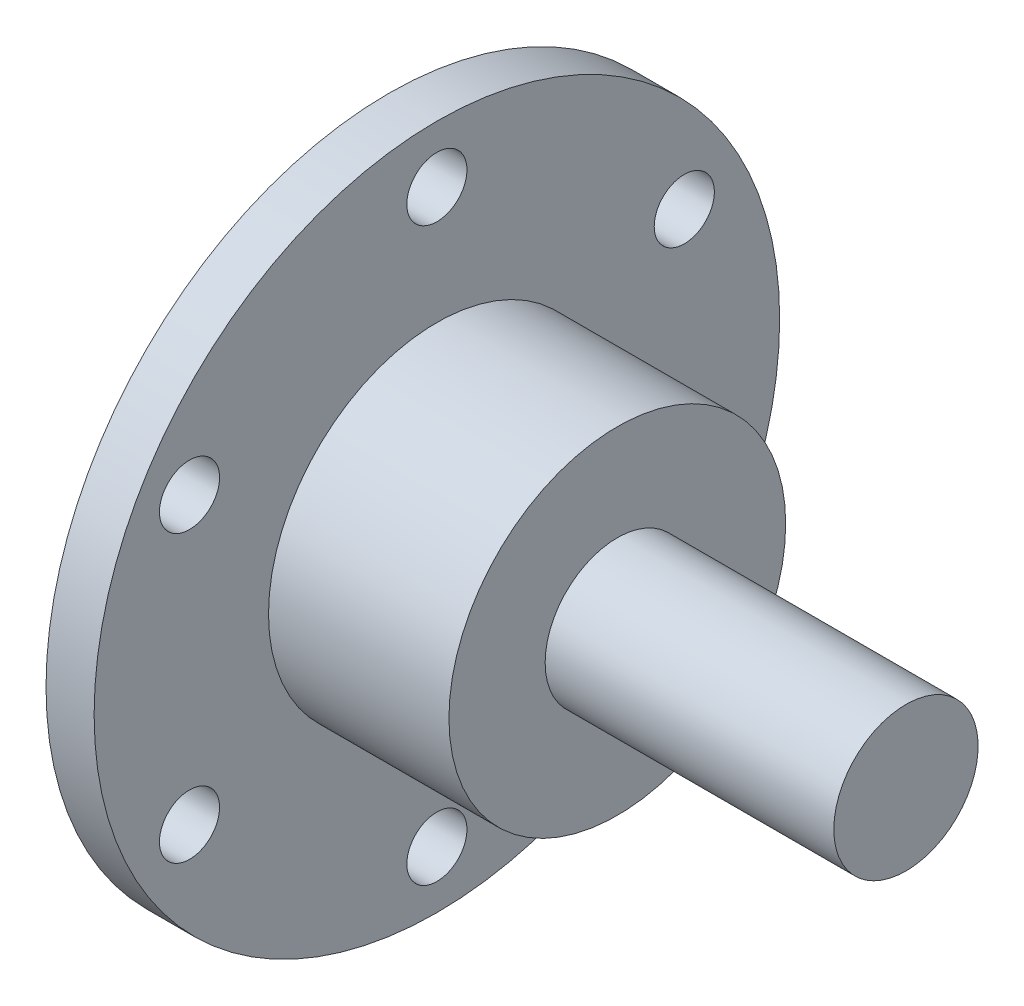
SolidWorks part; units mm, degrees
ref_plane "Front Plane" through (0, 0, 0) normal (0, 0, 1) x (1, 0, 0)
ref_plane "Top Plane" through (0, 0, 0) normal (0, 1, 0) x (1, 0, 0)
ref_plane "Right Plane" through (0, 0, 0) normal (1, 0, 0) x (0, 0, -1)
sketch "Sketch1" plane through (0, 0, 0) normal (0, 1, 0) x (1, 0, 0)
  line L0 (-51.7044, 0) -> (59.7922, 0) construction
  line L1 (0, 0) -> (0, 28.5)
  line L2 (0, 28.5) -> (4, 28.5)
  line L3 (4, 28.5) -> (4, 14)
  line L4 (4, 14) -> (19, 14)
  line L5 (19, 14) -> (19, 6)
  line L6 (19, 6) -> (43, 6)
  line L7 (43, 6) -> (43, 0)
  line L8 (0, 0) -> (43, 0)
  dimension "D1" = 28.5
  dimension "D2" = 14
  dimension "D3" = 6
  dimension "D4" = 4
  dimension "D5" = 15
  dimension "D6" = 24
revolve "Revolve1" add sketch "Sketch1" angle 360 about L0
sketch "Sketch2" plane through (0, 0, 0) normal (-1, 0, 0) x (0, 0, 1)
  circle A0 centre (0, 0) radius 23.75 construction
  circle A1 centre (0, 23.75) radius 2.5
  circle A2 centre (20.5681, 11.875) radius 2.5
  circle A3 centre (20.5681, -11.875) radius 2.5
  circle A4 centre (0, -23.75) radius 2.5
  circle A5 centre (-20.5681, -11.875) radius 2.5
  circle A6 centre (-20.5681, 11.875) radius 2.5
  point P17 (0, 0)
  dimension "D1" = 47.5
  dimension "D2" = 5
  dimension "D3" = 6
extrude "Cut-Extrude1" cut sketch "Sketch2" against normal up to next
